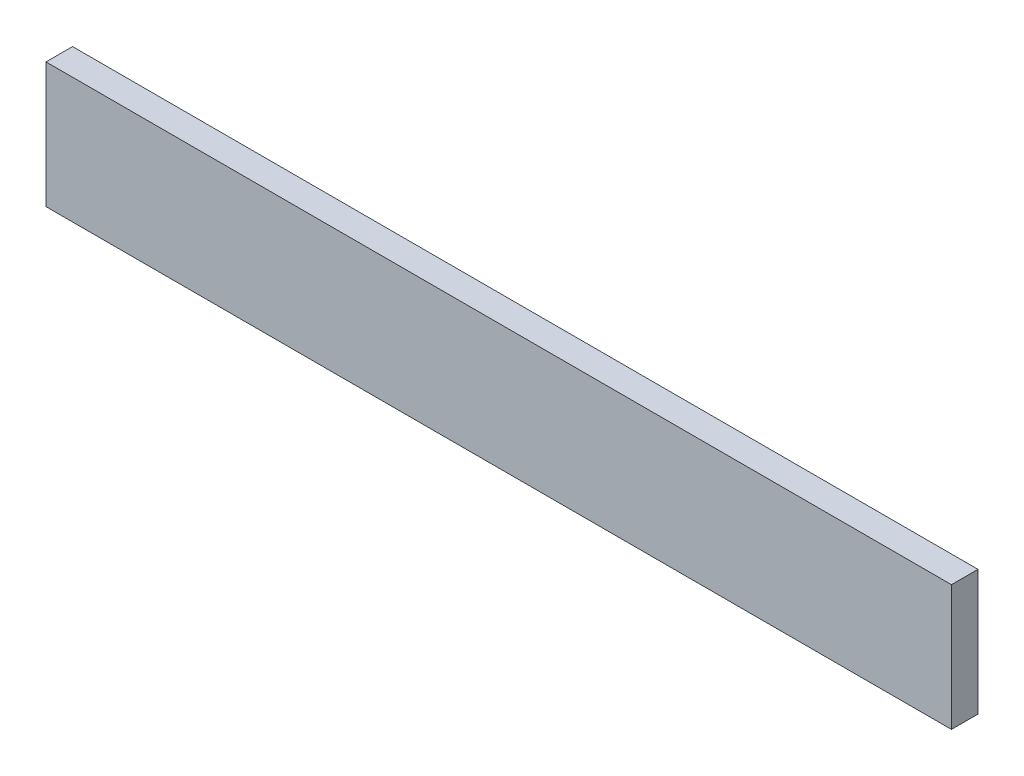
SolidWorks part; units mm, degrees
ref_plane "Front Plane" through (0, 0, 0) normal (0, 0, 1) x (1, 0, 0)
ref_plane "Top Plane" through (0, 0, 0) normal (0, 1, 0) x (1, 0, 0)
ref_plane "Right Plane" through (0, 0, 0) normal (1, 0, 0) x (0, 0, -1)
sketch "Sketch1" plane through (0, 0, 0) normal (0, 0, 1) x (1, 0, 0)
  line L1 (-325, 0) -> (325, 0)
  line L2 (-325, 0) -> (-325, 90)
  line L3 (-325, 90) -> (325, 90)
  line L4 (325, 0) -> (325, 90)
  dimension "D1" = 90
  dimension "D2" = 650
extrude "Boss-Extrude1" add sketch "Sketch1" along normal blind 19.05
